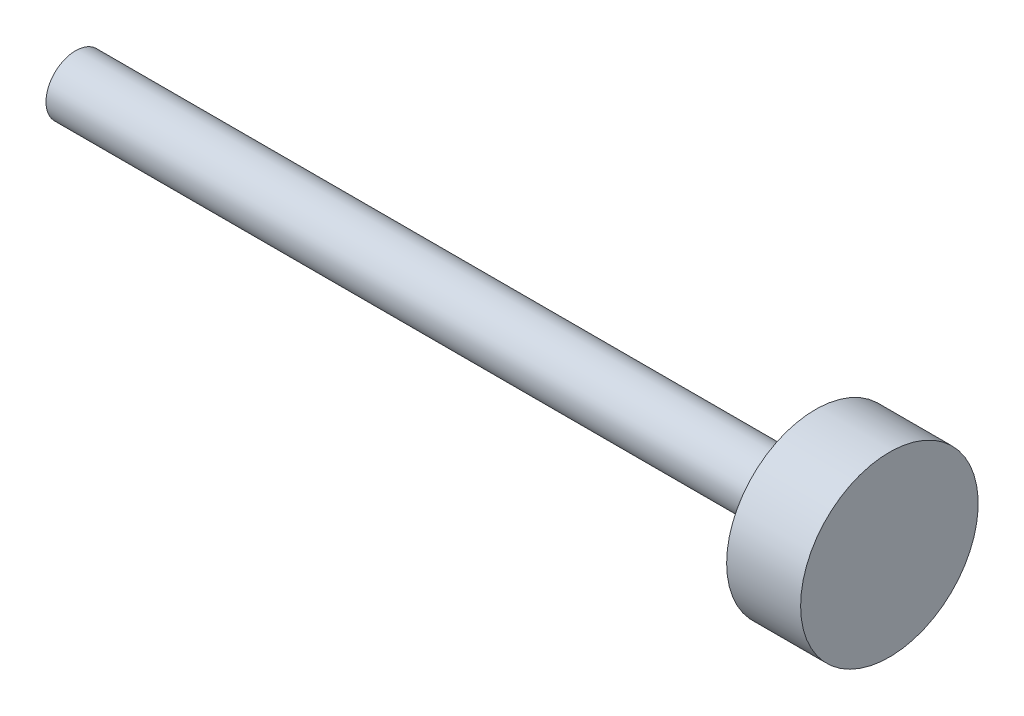
SolidWorks part; units mm, degrees
ref_plane "Plan de face" through (0, 0, 0) normal (0, 0, 1) x (1, 0, 0)
ref_plane "Plan de dessus" through (0, 0, 0) normal (0, 1, 0) x (1, 0, 0)
ref_plane "Plan de droite" through (0, 0, 0) normal (1, 0, 0) x (0, 0, -1)
sketch "Esquisse1" plane through (0, 0, 0) normal (0, 0, 1) x (1, 0, 0)
  line L0 (-51.8954, 0) -> (58.1046, 0) construction
  line L1 (58.1046, 0) -> (58.1046, 12)
  line L2 (58.1046, 12) -> (48.1046, 12)
  line L3 (48.1046, 12) -> (48.1046, 4)
  line L4 (48.1046, 4) -> (-51.8954, 4)
  line L5 (-51.8954, 4) -> (-51.8954, 0)
  line L6 (-51.8954, 0) -> (58.1046, 0)
  dimension "D1" = 12
  dimension "D2" = 100
  dimension "D3" = 10
  dimension "D4" = 4
revolve "Révolution1" add sketch "Esquisse1" angle 360 about L6
